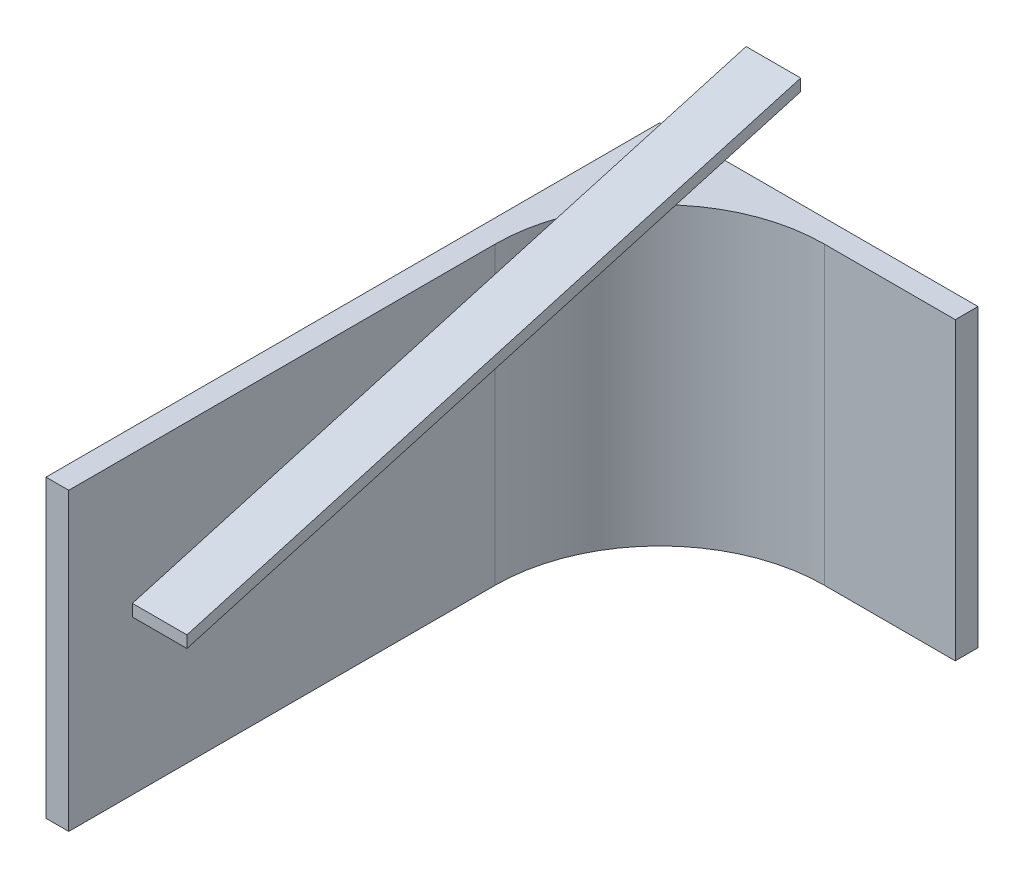
SolidWorks part; units mm, degrees
ref_plane "Front Plane" through (0, 0, 0) normal (0, 0, 1) x (1, 0, 0)
ref_plane "Top Plane" through (0, 0, 0) normal (0, 1, 0) x (1, 0, 0)
ref_plane "Right Plane" through (0, 0, 0) normal (1, 0, 0) x (0, 0, -1)
sketch "Sketch1" plane through (0, 0, 0) normal (0, 1, 0) x (1, 0, 0)
  line L0 (0, 65) -> (-65, 65)
  line L1 (-65, 65) -> (-65, -65)
  line L2 (-65, -65) -> (-70, -65)
  line L3 (-70, -65) -> (-70, 70)
  line L4 (-70, 70) -> (0, 70)
  line L5 (0, 70) -> (0, 65)
  line L6 (0, 65) -> (0, 0) construction
  line L7 (0, 0) -> (-65, 0) construction
  line L8 (-70, 70) -> (-65, 65) construction
  line L9 (-65, 43.7868) -> (-43.7868, 65) construction
  line L10 (-65, 65) -> (-54.3934, 54.3934) construction
  circle A0 centre (-28.7868, 28.7868) radius 36.2132
  dimension "D1" = 5
  dimension "D2" = 5
  dimension "D3" = 65
  dimension "D4" = 130
  dimension "D5" = 15
extrude "Boss-Extrude1" add sketch "Sketch1" against normal blind 65
sketch "Sketch2" plane through (0, 0, 0) normal (0, 1, 0) x (1, 0, 0)
  line L1 (-51, 70) -> (-39, 70)
  line L2 (-51, 70) -> (-51, -65)
  line L3 (-51, -65) -> (-39, -65)
  line L4 (-39, 70) -> (-39, -65)
  line L5 (-65, -65) -> (-51, -65) construction
  line L8 (-70, 70) -> (0, 70) construction
  line L9 (-45, -65) -> (-45, 70) construction
  line L10 (-65, 28.7868) -> (-65, -65) construction
  dimension "D1" = 12
  dimension "D2" = 20
sketch "Sketch3" plane through (-70, 0, 0) normal (-1, 0, 0) x (0, 0, 1)
  line L0 (-70, 21.4286) -> (65, -17.1429)
  line L1 (65, -17.1429) -> (65, -14.5428)
  line L2 (65, -14.5428) -> (-70, 24.0286)
  line L3 (-70, 24.0286) -> (-70, 21.4286)
  line L4 (-70, 0) -> (-70, 21.4286) construction
  line L5 (65, 0) -> (65, -17.1429) construction
  line L6 (65, 0) -> (-70, 0) construction
  line L8 (5, 0) -> (-70, 0) construction
  line L9 (-65, 20) -> (-65, 0) construction
  dimension "D1" = 2.5
  dimension "D2" = 5
  dimension "D3" = 75
  dimension "D4" = 20
extrude "Boss-Extrude3" add sketch "Sketch3" against normal blind 12 from offset 19
